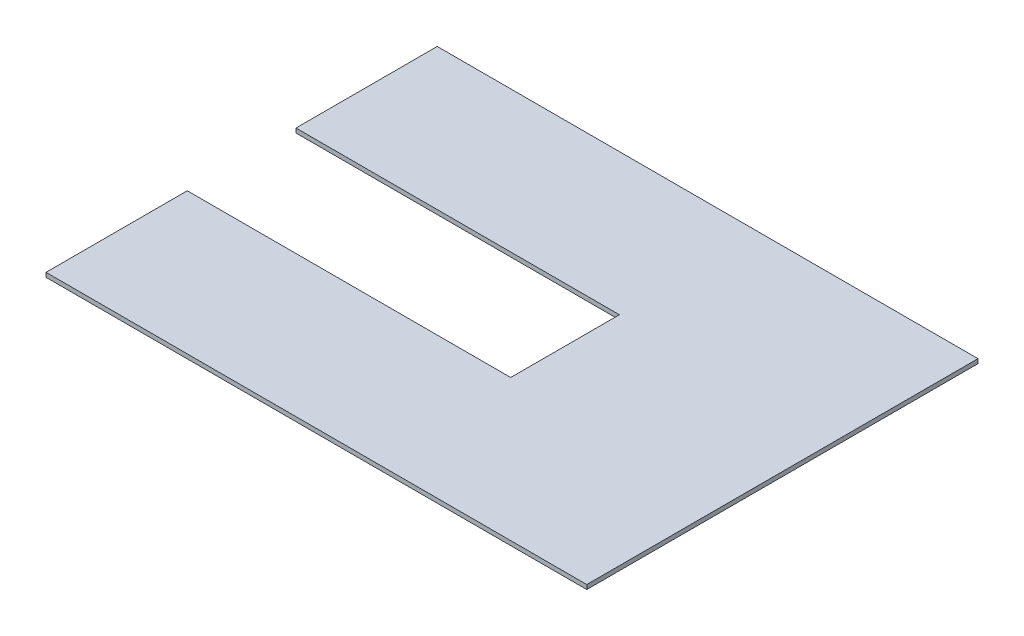
SolidWorks part; units mm, degrees
ref_plane "Front Plane" through (0, 0, 0) normal (0, 0, 1) x (1, 0, 0)
ref_plane "Top Plane" through (0, 0, 0) normal (0, 1, 0) x (1, 0, 0)
ref_plane "Right Plane" through (0, 0, 0) normal (1, 0, 0) x (0, 0, -1)
sketch "Sketch1" plane through (0, 0, 0) normal (0, 1, 0) x (1, 0, 0)
  line L0 (0, 0) -> (-124.4, 0) construction
  line L1 (-124.4, 90) -> (124.4, 90)
  line L2 (-124.4, 90) -> (-124.4, -90)
  line L3 (-124.4, -90) -> (124.4, -90)
  line L4 (124.4, 90) -> (124.4, -90)
  line L5 (-124.4, 90) -> (124.4, -90) construction
  line L6 (-124.4, -90) -> (124.4, 90) construction
  line L8 (24.4, 25) -> (-124.4, 25)
  line L9 (24.4, 25) -> (24.4, -25)
  line L10 (24.4, -25) -> (-124.4, -25)
  line L11 (-124.4, 25) -> (-124.4, -25)
  line L12 (24.4, 25) -> (-124.4, -25) construction
  line L13 (24.4, -25) -> (-124.4, 25) construction
  point P0 (0, 0)
  point P8 (-50, 0)
  dimension "D1" = 180
  dimension "D2" = 248.8
  dimension "D3" = 100
  dimension "D4" = 50
extrude "Boss-Extrude1" add sketch "Sketch1" along normal blind 2 contours L9 L10 L2 L3 L4 L1 L8
